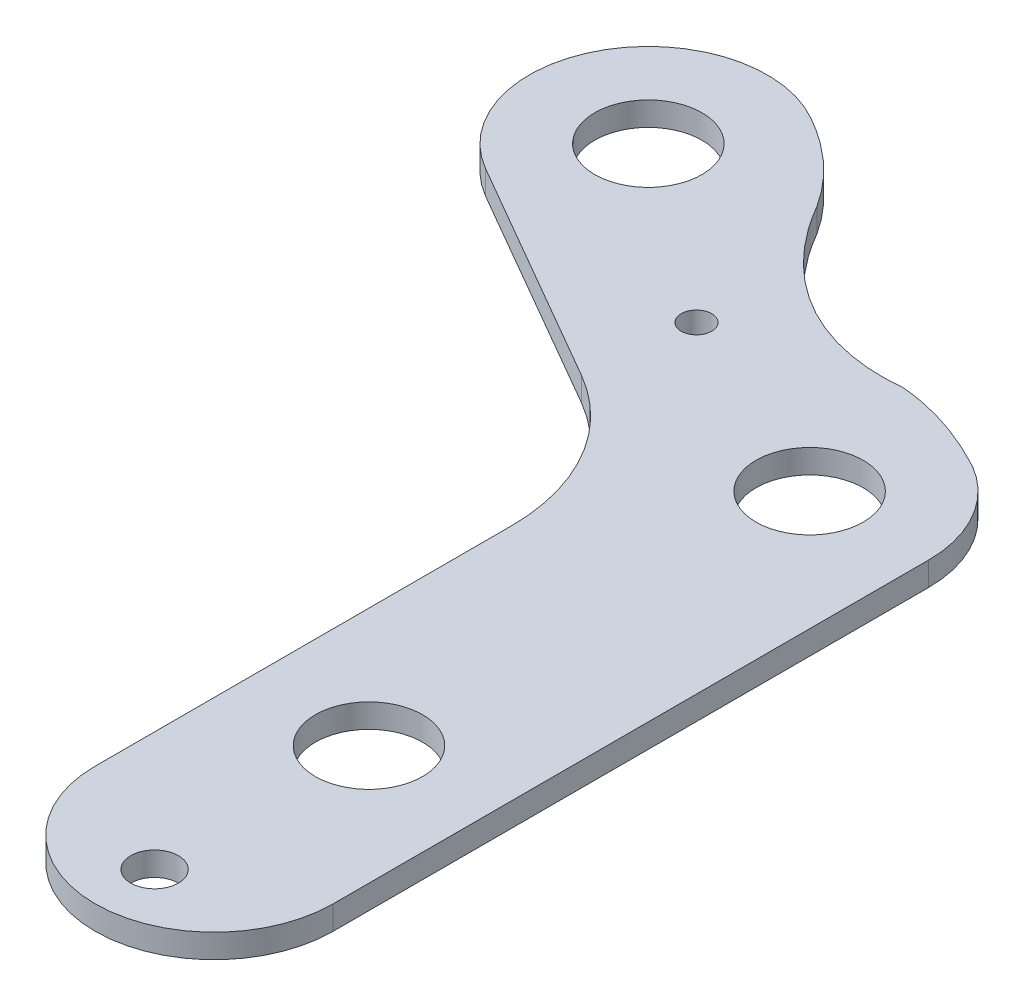
SolidWorks part; units mm, degrees
material "PC High Viscosity"
ref_plane "Front Plane" through (0, 0, 0) normal (0, 0, 1) x (1, 0, 0)
ref_plane "Top Plane" through (0, 0, 0) normal (0, 1, 0) x (1, 0, 0)
ref_plane "Right Plane" through (0, 0, 0) normal (1, 0, 0) x (0, 0, -1)
sketch "Sketch2" plane through (0, 0, 0) normal (0, 1, 0) x (1, 0, 0)
  line L0 (0, 117.475) -> (0, 0) construction
  line L1 (0, 117.475) -> (-101.7363, 176.2125) construction
  line L2 (31.75, 20.032) -> (31.75, 117.475)
  line L4 (-57.15, 113.8088) -> (-117.6113, 148.7162)
  line L5 (-59.6527, 249.1035) -> (-151.7481, 89.5896) construction
  line L6 (-85.8613, 203.7088) -> (15.875, 144.9713) construction
  line L7 (59.941, 221.2959) -> (-45.6102, 38.4758) construction
  line L8 (-50.8682, 146.8437) -> (-34.9932, 174.3401) construction
  line L9 (-34.9932, 174.3401) -> (22.7698, 274.3885) construction
  line L10 (-31.75, -41.275) -> (-31.75, 69.8147)
  line L11 (31.75, 20.032) -> (31.75, -41.275)
  circle A1 centre (0, 0) radius 14.2875
  circle A2 centre (0, 117.475) radius 14.2875
  circle A3 centre (-101.7363, 176.2125) radius 14.2875
  arc A5 (-117.6113, 148.7162) -> (-85.8613, 203.7088) centre (-101.7363, 176.2125) cw
  arc A6 (31.75, 117.475) -> (15.875, 144.9713) centre (0, 117.475) ccw
  arc A7 (-31.75, 69.8147) -> (-57.15, 113.8088) centre (-82.55, 69.8147) ccw
  circle A8 centre (-101.7363, 176.2125) radius 50.8 construction
  circle A9 centre (0, 117.475) radius 50.8 construction
  arc A12 (31.75, -41.275) -> (-31.75, -41.275) centre (0, -41.275) cw
  circle A16 centre (0, -57.15) radius 6.35
  circle A17 centre (-54.0432, 141.3445) radius 4.064
  spline S0 degree 2 poles (-85.8613, 203.7088) (-72.3863, 196.1044) (-64.7835, 184.2072) knots 0 0 0 1 1 1
  spline S1 degree 2 poles (-11.4264, 153.8358) (1.2245, 152.856) (15.875, 144.9713) knots 0 0 0 1 1 1
  spline S2 degree 3 poles (-64.7835, 184.2072) (-52.4235, 162.7716) (-33.1837, 151.6277) (-11.4264, 153.8358) knots 0 0 0 0 1 1 1 1
  dimension "D2" = 28.575
  dimension "1.125" = 28.575
  dimension "D6" = 31.75
  dimension "D7" = 101.6
  dimension "D8" = 41.275
  dimension "D9" = 50.8
  dimension "D10" = 12.7
  dimension "D11" = 61.3955
  dimension "D3" = 31.75
  dimension "D13" = 117.475
  dimension "1.25" = 12.7
  dimension "D4" = 8.128
  dimension "D5" = 117.475
  dimension "0.5" = 11.9476
  dimension "D14" = 6.35
  dimension "D15" = 57.15
extrude "Boss-Extrude1" add sketch "Sketch2" along normal blind 6.35
